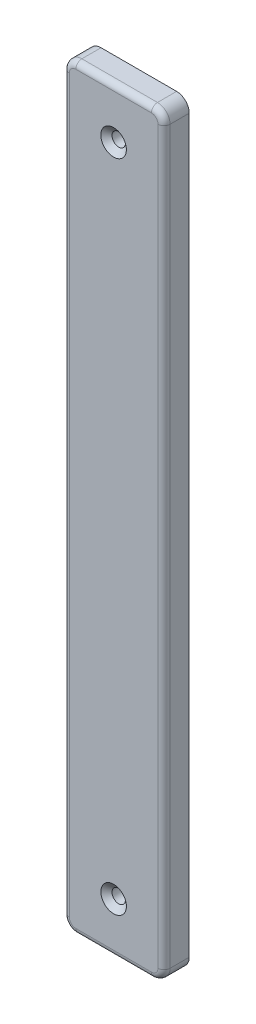
SolidWorks part; units mm, degrees
ref_plane "Front" through (0, 0, 0) normal (0, 0, 1) x (1, 0, 0)
ref_plane "Top" through (0, 0, 0) normal (0, 1, 0) x (1, 0, 0)
ref_plane "Right" through (0, 0, 0) normal (1, 0, 0) x (0, 0, -1)
sketch "Sketch1" plane through (0, 0, 0) normal (0, 0, 1) x (1, 0, 0)
  line L0 (0, 190.5) -> (0, -190.5) construction
  line L1 (25.4, -190.5) -> (-25.4, -190.5)
  line L2 (25.4, -190.5) -> (25.4, 190.5)
  line L3 (-25.4, 190.5) -> (25.4, 190.5)
  line L4 (-25.4, 190.5) -> (-25.4, -190.5)
  dimension "D1" = 381
  dimension "D3" = 50.8
extrude "Base-Extrude" add sketch "Sketch1" along normal blind 12.7
sketch "Sketch2" plane through (0, 0, 12.7) normal (0, 0, 1) x (1, 0, 0)
  line L0 (0, 0) -> (71.1, 0) construction
  line L1 (0, 190.5) -> (0, -190.5) construction
  line L2 (-25.4, 190.5) -> (25.4, 190.5) construction
  line L3 (25.4, -190.5) -> (-25.4, -190.5) construction
  point P0 (0, -165.1)
  point P2 (0, 165.1)
  dimension "D1" = 330.2
hole_wizard "CSK for 1/4 Flat Head Machine Screw (100)1" positions "Sketch5" profile "Sketch4" countersink size "1/4" standard "Ansi Inch" end condition through all
sketch "Sketch5" plane through (0, 0, 12.7) normal (0, 0, 1) x (1, 0, 0)
  point P0 (0, 165.1)
  point P1 (0, -165.1)
sketch "Sketch4" plane through (0, 165.1, 12.7) normal (1, 0, 0) x (0, -1, 0)
  line L0 (0, 0) -> (0, 12.7)
  line L1 (0, 12.7) -> (3.3782, 12.7)
  line L2 (3.3782, 12.7) -> (3.3782, 2.5682)
  line L3 (3.3782, 2.5682) -> (6.4389, 0)
  line L5 (6.4389, 0) -> (0, 0)
  line L6 (-3.3782, 2.5682) -> (-6.4389, 0) construction
  line L11 (0, -6.35) -> (0, 107.95) construction
  dimension "Thru Hole Dia." = 6.7564
  dimension "Thru Hole Depth" = 12.7
  dimension "Near C'Sink Dia." = 12.8778
  dimension "Near C'Sink Angle" = 100
fillet "Fillet1" radius 6.35 4 edges at (25.4, -190.5, 6.35) (-25.4, -190.5, 6.35) (-25.4, 190.5, 6.35) (25.4, 190.5, 6.35)
fillet "Fillet2" radius 3.048 8 edges at (-23.5401, 188.6401, 12.7) (0, 190.5, 12.7) (23.5401, 188.6401, 12.7) (25.4, 0, 12.7) (23.5401, -188.6401, 12.7) (0, -190.5, 12.7) (-23.5401, -188.6401, 12.7) (-25.4, 0, 12.7)
